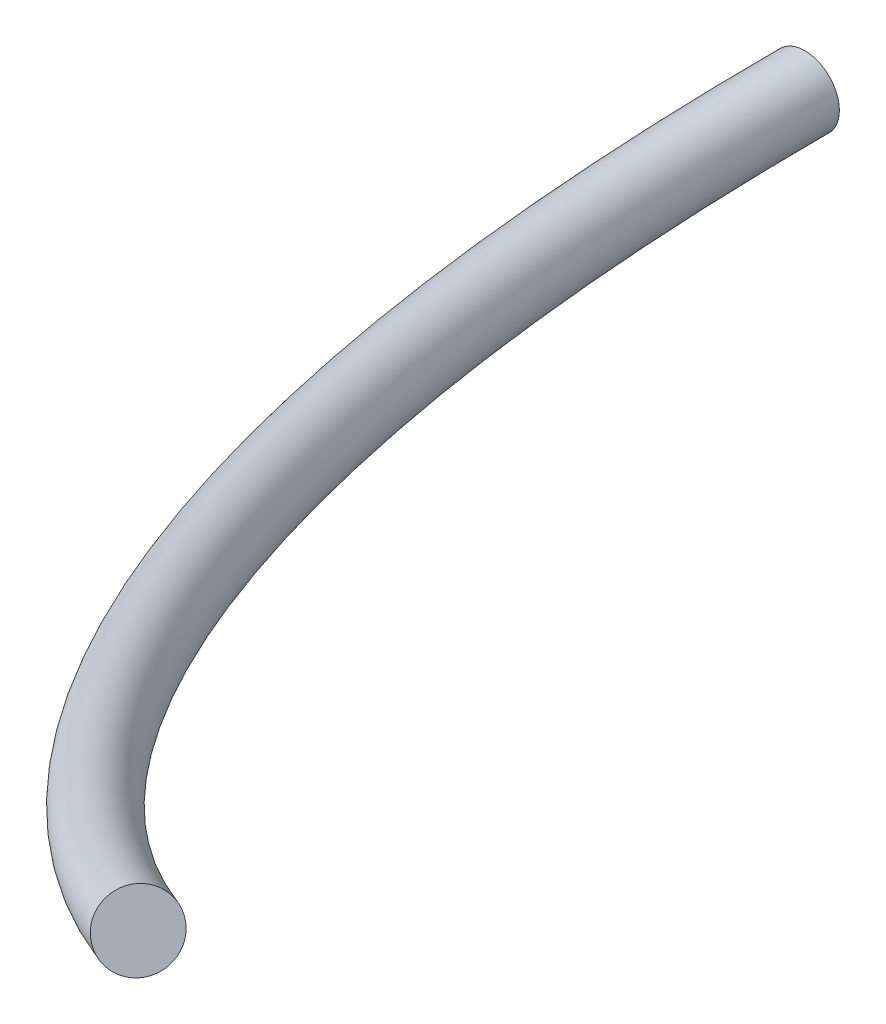
SolidWorks part; units mm, degrees
ref_plane "Front" through (0, 0, 0) normal (0, 0, 1) x (1, 0, 0)
ref_plane "Top" through (0, 0, 0) normal (0, 1, 0) x (1, 0, 0)
ref_plane "Right" through (0, 0, 0) normal (1, 0, 0) x (0, 0, -1)
sketch "Sketch1" plane through (0, 0, 0) normal (0, 0, 1) x (1, 0, 0)
  circle A0 centre (-2842.3447, -17556.3169) radius 50.8
ref_plane "Plane1" through (6061.8056, -13582.4105, 0) normal (-0.4076, 0.9132, 0) x (-0.9132, -0.4075, -0.0049)
sketch "Sketch2" plane through (6061.8056, -13582.4105, 0) normal (-0.4076, 0.9132, 0) x (-0.9132, -0.4075, -0.0049)
  line L0 (8592.479, 2072.3016) -> (3678.0635, 4994.3012) construction
  line L1 (9750.5651, 48.0147) -> (9747.4731, 675.9188) construction
  arc A0 (9750.5651, 48.0147) -> (8592.479, 2072.3016) centre (7381.949, 36.3509) ccw
  dimension "D1" = 2438.4
sweep "Sweep1" add profiles "Sketch1" path "Sketch2"
